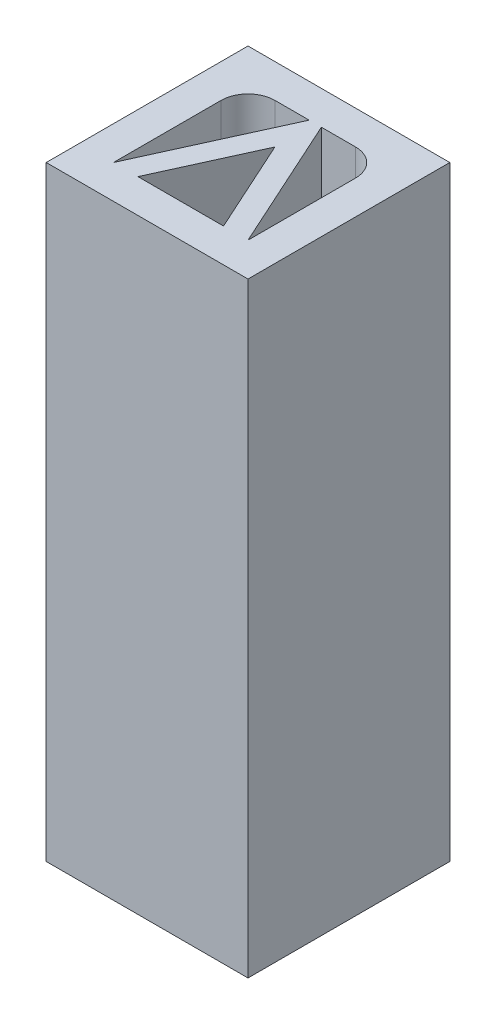
SolidWorks part; units mm, degrees
ref_plane "Front Plane" through (0, 0, 0) normal (0, 0, 1) x (1, 0, 0)
ref_plane "Top Plane" through (0, 0, 0) normal (0, 1, 0) x (1, 0, 0)
ref_plane "Right Plane" through (0, 0, 0) normal (1, 0, 0) x (0, 0, -1)
sketch "Sketch1" plane through (0, 0, 0) normal (0, 1, 0) x (1, 0, 0)
  line L0 (7.5, 15) -> (7.5, 12.5) construction
  line L1 (0, 0) -> (15, 0)
  line L2 (0, 0) -> (0, 15)
  line L3 (0, 15) -> (15, 15)
  line L4 (15, 0) -> (15, 15)
  line L5 (2.5, 12.5) -> (12.5, 12.5)
  line L6 (2.5, 12.5) -> (2.5, 2.5)
  line L7 (2.5, 2.5) -> (12.5, 2.5)
  line L8 (12.5, 12.5) -> (12.5, 2.5)
  line L9 (0, 7.5) -> (2.5, 7.5) construction
  dimension "D1" = 15
  dimension "D2" = 15
  dimension "D3" = 2.5
  dimension "D4" = 2.5
extrude "Boss-Extrude1" add sketch "Sketch1" along normal blind 45
sketch "Sketch3" plane through (0, 0, 0) normal (0, -1, 0) x (1, 0, 0)
  line L0 (12.5, -2.5) -> (7.5, -13.5)
  line L2 (7.5, -13.5) -> (2.5, -2.5)
  line L3 (7.5, -13.5) -> (7.5, -2.5) construction
  line L4 (2.5, -2.5) -> (12.5, -2.5) construction
  line L5 (12.5, -2.5) -> (10.6818, -2.5)
  line L6 (10.6818, -2.5) -> (7.5, -9.5)
  line L7 (7.5, -9.5) -> (4.3182, -2.5)
  line L8 (4.3182, -2.5) -> (2.5, -2.5)
  line L9 (12.5, -12.5) -> (2.5, -12.5) construction
  dimension "D1" = 4
  dimension "D2" = 1
extrude "Boss-Extrude4" add sketch "Sketch3" against normal through all
fillet "Fillet2" radius 2 2 edges at (2.5, 22.5, -12.5) (12.5, 22.5, -12.5)
